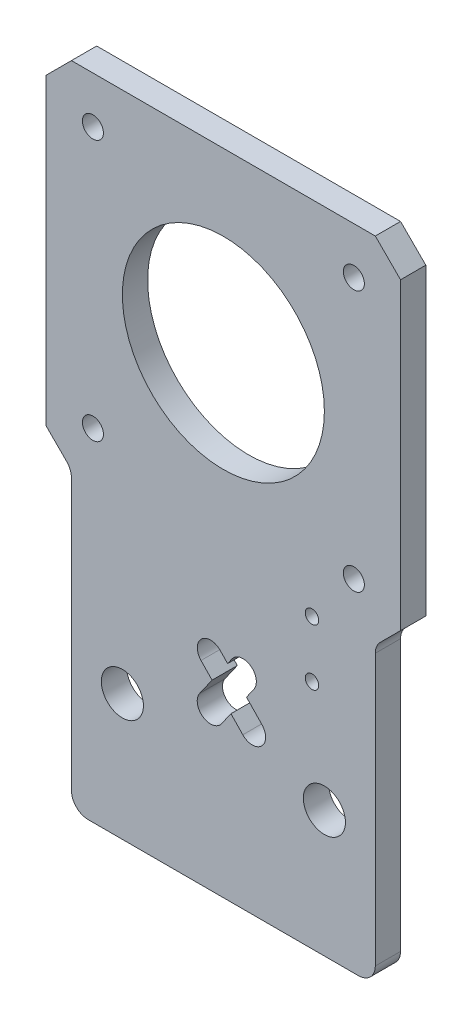
SolidWorks part; units mm, degrees
ref_plane "Plano frontal" through (0, 0, 0) normal (0, 0, 1) x (1, 0, 0)
ref_plane "Plano superior" through (0, 0, 0) normal (0, 1, 0) x (1, 0, 0)
ref_plane "Plano direito" through (0, 0, 0) normal (1, 0, 0) x (0, 0, -1)
sketch "Sketch1" plane through (0, 0, 0) normal (0, 0, 1) x (1, 0, 0)
  line L0 (149.1978, -56.055) -> (-642.8022, -56.055) construction
  line L2 (18.05, -56.055) -> (18.05, -21.05)
  line L4 (-18.05, -56.055) -> (-18.05, -21.05)
  line L5 (18.05, -56.055) -> (-18.05, -56.055)
  line L16 (-21.05, -18.05) -> (-18.05, -21.05)
  line L18 (18.05, -21.05) -> (21.05, -18.05)
  line L19 (21.05, -18.05) -> (21.05, 18.05)
  line L20 (21.05, 18.05) -> (18.05, 21.05)
  line L21 (18.05, 21.05) -> (-18.05, 21.05)
  line L22 (-18.05, 21.05) -> (-21.05, 18.05)
  line L23 (-21.05, 18.05) -> (-21.05, -18.05)
  circle A3 centre (0, 0) radius 12
  dimension "D2" = 36.1
  dimension "D3" = 4.2426
extrude "Boss-Extrude1" add sketch "Sketch1" along normal blind 3
hole_wizard "Tap Drill for M3 Tap1" positions "Sketch3" profile "Sketch2" hole size "M3" standard "ISO"
sketch "Sketch3" plane through (0, 0, 3) normal (0, 0, 1) x (1, 0, 0)
  point P0 (-15.5, 15.5)
  point P3 (15.5, 15.5)
  point P6 (-15.5, -15.5)
  point P9 (15.5, -15.5)
sketch "Sketch2" plane through (-15.5, 15.5, 3) normal (1, 0, 0) x (0, -1, 0)
  line L0 (0, 0) -> (0, 5.7511)
  line L1 (0, 5.7511) -> (1.25, 5)
  line L2 (1.25, 5) -> (1.25, 0)
  line L5 (1.25, 0) -> (0, 0)
  line L10 (0, 5.7511) -> (-1.25, 5) construction
  line L11 (0, -6.35) -> (0, 107.95) construction
  dimension "Hole Dia." = 2.5
  dimension "Hole Depth" = 5
  dimension "Drill Angle" = 118
hole_wizard "Tap Drill for M4 Tap1" positions "Sketch5" profile "Sketch4" hole size "M6" standard "ISO"
sketch "Sketch5" plane through (0, 0, 3) normal (0, 0, 1) x (1, 0, 0)
  line L1 (0, -56.055) -> (0, -21.05) construction
  line L2 (-18.05, -56.055) -> (18.05, -56.055) construction
  line L3 (149.1978, -41.055) -> (-642.8022, -41.055) construction
  point P40 (-12, -41.055)
  point P45 (12, -41.055)
  dimension "D1" = 12
sketch "Sketch4" plane through (12, -41.055, 3) normal (1, 0, 0) x (0, -1, 0)
  line L0 (0, 0) -> (0, 6.5022)
  line L1 (0, 6.5022) -> (2.5, 5)
  line L2 (2.5, 5) -> (2.5, 0)
  line L5 (2.5, 0) -> (0, 0)
  line L10 (0, 6.5022) -> (-2.5, 5) construction
  line L11 (0, -6.35) -> (0, 107.95) construction
  dimension "Hole Dia." = 5
  dimension "Hole Depth" = 5
  dimension "Drill Angle" = 118
fillet "Fillet1" radius 2 4 edges at (18.05, -21.05, 1.5) (18.05, -56.055, 1.5) (-18.05, -56.055, 1.5) (-18.05, -21.05, 1.5)
hole_wizard "Tap Drill for M2 Tap1" positions "Sketch7" profile "Sketch6" hole size "M2" standard "ISO"
sketch "Sketch7" plane through (0, 0, 3) normal (0, 0, 1) x (1, 0, 0)
  point P0 (10.5295, -21.8613)
  point P3 (10.5295, -28.5613)
sketch "Sketch6" plane through (10.5295, -21.8613, 3) normal (1, 0, 0) x (0, -1, 0)
  line L0 (0, 0) -> (0, 5.4807)
  line L1 (0, 5.4807) -> (0.8, 5)
  line L2 (0.8, 5) -> (0.8, 0)
  line L5 (0.8, 0) -> (0, 0)
  line L10 (0, 5.4807) -> (-0.8, 5) construction
  line L11 (0, -6.35) -> (0, 107.95) construction
  dimension "Hole Dia." = 1.6
  dimension "Hole Depth" = 5
  dimension "Drill Angle" = 118
sketch "Sketch8" plane through (0, 0, 0) normal (0, 0, 1) x (1, 0, 0)
  line L0 (9.1176, -56.055) -> (-8.1087, -56.055) construction
  line L1 (0.5044, -56.055) -> (0.5044, -38.2118) construction
  line L2 (0.8999, -36.6716) -> (-0.2213, -38.2661)
  line L3 (1.0288, -30.9682) -> (0.5043, -31.7142)
  line L4 (-2.6554, -32.9727) -> (-1.3417, -34.3396)
  line L7 (3.6261, -32.7944) -> (2.7458, -34.0463)
  line L11 (0.5044, -34.343) -> (0.5044, -20.8461) construction
  line L12 (0.8999, -36.6716) -> (2.3092, -38.1379)
  line L13 (4.5803, -35.9549) -> (2.7458, -34.0463)
  line L14 (0.5043, -31.7142) -> (-0.3843, -30.7898)
  line L15 (-1.3417, -34.3396) -> (-2.8185, -36.4399)
  arc A0 (3.6261, -32.7944) -> (1.0288, -30.9682) centre (2.3275, -31.8813) ccw
  arc A4 (-2.8185, -36.4399) -> (-0.2213, -38.2661) centre (-1.5199, -37.353) ccw
  arc A5 (-0.3843, -30.7898) -> (-2.6554, -32.9727) centre (-1.5199, -31.8813) ccw
  arc A6 (2.3092, -38.1379) -> (4.5803, -35.9549) centre (3.4448, -37.0464) ccw
  point P20 (0.4038, -34.6171)
  point P29 (-0.4429, -32.9927)
  point P30 (0.9624, -34.4638)
extrude "Cut-Extrude1" cut sketch "Sketch8" along normal blind 10
